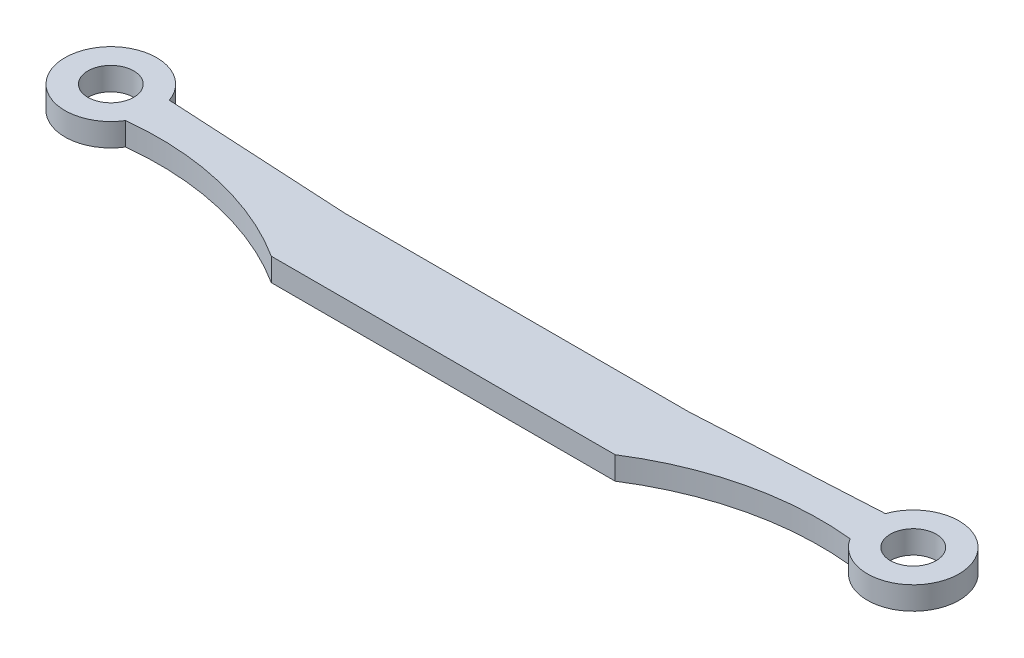
SolidWorks part; units mm, degrees
material "Cast Alloy Steel"
ref_plane "Front Plane" through (0, 0, 0) normal (0, 0, 1) x (1, 0, 0)
ref_plane "Top Plane" through (0, 0, 0) normal (0, 1, 0) x (1, 0, 0)
ref_plane "Right Plane" through (0, 0, 0) normal (1, 0, 0) x (0, 0, -1)
sketch "Sketch1" plane through (0, 0, 0) normal (0, 1, 0) x (1, 0, 0)
  line L0 (26.2297, -2.6641) -> (10, -3.5491)
  line L1 (0, 0) -> (34, 0)
  line L4 (34, 0) -> (34, -10)
  line L5 (10, -3.5491) -> (-10, -3.5491)
  line L6 (-10, -10) -> (10.4692, -10)
  line L7 (-26.2297, -2.6641) -> (-10, -3.5491)
  circle A0 centre (30, -4) radius 4
  arc A1 (10, -10) -> (26.5966, -6.1016) centre (23.8689, -31.7667) cw
  circle A2 centre (30, -4) radius 2
  circle A3 centre (-30, -4) radius 2
  circle A4 centre (-30, -4) radius 4
  arc A5 (-10, -10) -> (-26.5966, -6.1016) centre (-23.8689, -31.7667) ccw
  point P7 (10, -10)
  dimension "D5" = 8
  dimension "D7" = 4
  dimension "D2" = 10
  dimension "D3" = 4
  dimension "D4" = 4
extrude "Boss-Extrude1" add sketch "Sketch1" along normal blind 2 contours A5 L6 A1 A0 L0 L5 L7 A4 | A4 A3 | A0 A2
sketch "Sketch3" plane through (0, 2, 0) normal (0, 1, 0) x (1, 0, 0)
  line L0 (-10, -10) -> (10, -10) construction
  line L1 (0, -10) -> (-40.7992, -10)
  line L2 (0, -10) -> (0, 0.7917)
  line L3 (0, 0.7917) -> (-40.7992, 0.7917)
  line L4 (-40.7992, -10) -> (-40.7992, 0.7917)
extrude "Cut-Extrude1" cut sketch "Sketch3" against normal blind 10
sketch "Sketch4" plane through (0, 2, 0) normal (0, 1, 0) x (1, 0, 0)
  line L1 (0, -3.5491) -> (-4.995, -3.5491)
  line L2 (0, -3.5491) -> (0, -10)
  line L3 (0, -10) -> (-4.995, -10)
  line L4 (-4.995, -3.5491) -> (-4.995, -10)
  dimension "D1" = 4.995
extrude "Boss-Extrude2" add sketch "Sketch4" against normal blind 2
ref_plane "Plane2" through (-4.995, 0, 0) normal (-1, 0, 0) x (0, 0, 1)
mirror "Mirror3" about plane through (-4.995, 0, 0) normal (-1, 0, 0) of bodies 103
